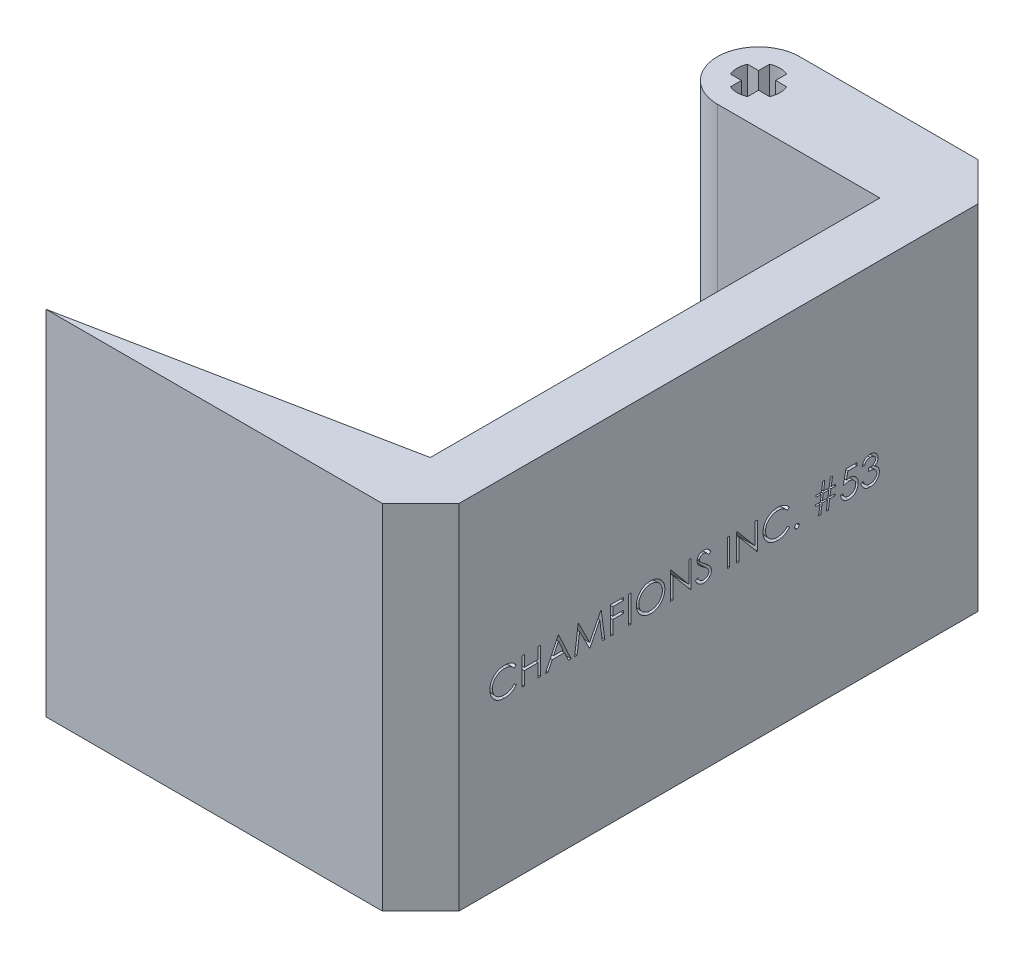
SolidWorks part; units mm, degrees
ref_plane "Front Plane" through (0, 0, 0) normal (0, 0, 1) x (1, 0, 0)
ref_plane "Top Plane" through (0, 0, 0) normal (0, 1, 0) x (1, 0, 0)
ref_plane "Right Plane" through (0, 0, 0) normal (1, 0, 0) x (0, 0, -1)
sketch "Sketch1" plane through (0, 0, 0) normal (0, 1, 0) x (1, 0, 0)
  line L0 (-1, 1) -> (-2.2913, 1)
  line L1 (-1, -1) -> (-2.2913, -1)
  line L2 (1, 1) -> (1, 2.2913)
  line L3 (-1, 1) -> (-1, 2.2913)
  line L4 (1, -1) -> (2.2913, -1)
  line L5 (1, 1) -> (2.2913, 1)
  line L6 (-1, -1) -> (-1, -2.2913)
  line L7 (1, -1) -> (1, -2.2913)
  line L8 (25.4, 4.826) -> (0, 4.826)
  line L9 (19.05, -4.826) -> (0, -4.826)
  line L10 (25.4, 4.826) -> (25.4, -65.024)
  line L11 (25.4, -65.024) -> (-18.542, -65.024)
  line L12 (-18.542, -65.024) -> (19.05, -57.5506)
  line L13 (19.05, -57.5506) -> (19.05, -4.826)
  arc A0 (-2.2913, 1) -> (-2.2913, -1) centre (0, 0) ccw
  arc A1 (1, 2.2913) -> (-1, 2.2913) centre (0, 0) ccw
  arc A2 (2.2913, -1) -> (2.2913, 1) centre (0, 0) ccw
  arc A3 (-1, -2.2913) -> (1, -2.2913) centre (0, 0) ccw
  arc A4 (0, -4.826) -> (0, 4.826) centre (0, 0) cw
  point P13 (0, 0)
  dimension "D1" = 5
  dimension "D7" = 4.826
  dimension "D8" = 57.5506
  dimension "D2" = 1
  dimension "D3" = 6.35
  dimension "D4" = 69.85
  dimension "D5" = 25.4
  dimension "D6" = 43.942
extrude "Boss-Extrude6" add sketch "Sketch1" along normal blind 41.402
sketch "Sketch2" plane through (0, 0, 0) normal (0, 1, 0) x (1, 0, 0)
  line L0 (25.4, -60.5339) -> (20.9099, -65.024)
  line L1 (25.4, -65.024) -> (25.4, 4.826) construction
  line L2 (-18.542, -65.024) -> (25.4, -65.024) construction
  line L3 (25.4, 0.3359) -> (20.9099, 4.826)
  line L4 (25.4, 4.826) -> (0, 4.826) construction
  line L8 (25.4, -60.5339) -> (25.4, -65.024)
  line L9 (20.9099, -65.024) -> (25.4, -65.024)
  line L10 (20.9099, 4.826) -> (25.4, 4.826)
  line L11 (25.4, 4.826) -> (25.4, 0.3359)
  dimension "D1" = 6.35
extrude "Cut-Extrude1" cut sketch "Sketch2" along normal through all
sketch "Sketch3" plane through (0, 0, 0) normal (1, 0, 0) x (0, 0, -1)
  text T0 "CHAMFIONS INC. #53"
extrude "Cut-Extrude2" cut sketch "Sketch3" against normal through all both and the other way through all
